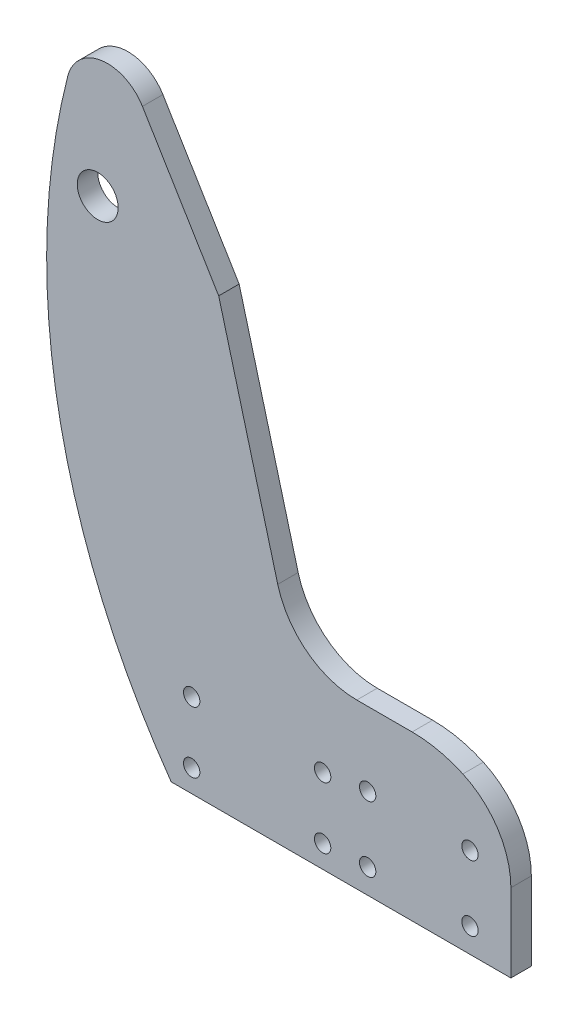
SolidWorks part; units mm, degrees
ref_plane "前视基准面" through (0, 0, 0) normal (0, 0, 1) x (1, 0, 0)
ref_plane "上视基准面" through (0, 0, 0) normal (0, 1, 0) x (1, 0, 0)
ref_plane "右视基准面" through (0, 0, 0) normal (1, 0, 0) x (0, 0, -1)
sketch "草图1" plane through (0, 0, 0) normal (0, 0, 1) x (1, 0, 0)
  line L1 (41.5, -14) -> (-41.5, -14)
  line L2 (41.5, -14) -> (41.5, 14)
  line L3 (41.5, 14) -> (-41.5, 14)
  line L4 (-41.5, -14) -> (-41.5, 14)
  line L5 (41.5, -14) -> (-41.5, 14) construction
  line L6 (41.5, 14) -> (-41.5, -14) construction
  point P0 (0, 0)
  dimension "D1" = 28
  dimension "D2" = 83
extrude "凸台-拉伸1" add sketch "草图1" along normal blind 5
sketch "草图2" plane through (0, 0, 5) normal (0, 0, 1) x (1, 0, 0)
  line L0 (-41.5, -14) -> (41.5, -14) construction
  line L1 (41.5, 14) -> (-41.5, 14) construction
  line L2 (41.5, -14) -> (41.5, 14) construction
  circle A0 centre (6.5, 8) radius 2
  circle A1 centre (31.5, 8) radius 2
  circle A2 centre (31.5, -8) radius 2
  circle A3 centre (6.5, -8) radius 2
  dimension "D1" = 25
  dimension "D2" = 25
  dimension "D3" = 6
  dimension "D4" = 6
  dimension "D5" = 10
  dimension "D6" = 10
  dimension "D7" = 4
  dimension "D8" = 4
  dimension "D9" = 4
  dimension "D10" = 4
  dimension "D11" = 6
  dimension "D12" = 6
extrude "切除-拉伸1" cut sketch "草图2" against normal through all
sketch "草图3" plane through (0, 0, 0) normal (0, 0, -1) x (-1, 0, 0)
  line L0 (41.5, 14) -> (59.7703, 144)
  line L1 (59.7703, 144) -> (29.5, 94)
  line L2 (29.5, 94) -> (-41.5, 14)
  line L3 (-41.5, 14) -> (41.5, 14) construction
  line L4 (41.5, 14) -> (-41.5, 14)
  line L5 (41.5, 14) -> (41.5, -14) construction
  dimension "D1" = 98
  dimension "D2" = 130
  dimension "D3" = 80
  dimension "D4" = 12
extrude "凸台-拉伸2" add sketch "草图3" against normal blind 5
sketch "草图5" plane through (0, 0, 5) normal (0, 0, 1) x (1, 0, 0)
  line L0 (36.5, 26) -> (-11.5, 26)
  line L1 (41.5, -14) -> (41.5, 14) construction
  line L2 (-35.6025, 115.9516) -> (36.5, 26)
  line L3 (-41.5, -14) -> (41.5, -14) construction
  line L5 (-35.6025, 115.9516) -> (-11.5, 26)
  point P6 (-40.6025, 113.9516)
  dimension "D1" = 40
  dimension "D2" = 53
  dimension "D3" = 105
extrude "切除-拉伸3" cut sketch "草图5" against normal through all
fillet "圆角4" radius 30 1 edges at (30.85, 26, 2.5)
fillet "圆角5" radius 20 1 edges at (-11.5, 26, 2.5)
sketch "草图6" plane through (0, 0, 5) normal (0, 0, 1) x (1, 0, 0)
  line L0 (-41.5, 14) -> (-41.5, -14) construction
  line L1 (-41.5, -14) -> (41.5, -14) construction
  circle A0 centre (-36.5, -8.5) radius 2
  circle A1 centre (-4.5, -8.5) radius 2
  circle A2 centre (-4.5, 6.5) radius 2
  circle A3 centre (-36.5, 6.5) radius 2
  dimension "D1" = 5
  dimension "D2" = 37
  dimension "D3" = 37
  dimension "D4" = 5
  dimension "D5" = 15
  dimension "D6" = 15
  dimension "D7" = 4
  dimension "D8" = 4
  dimension "D9" = 4
  dimension "D10" = 4
  dimension "D11" = 5.5
  dimension "D12" = 5.5
extrude "切除-拉伸4" cut sketch "草图6" against normal through all
sketch "草图7" plane through (0, 0, 5) normal (0, 0, 1) x (1, 0, 0)
  line L0 (-41.5, 14) -> (-41.5, -14) construction
  line L1 (-41.5, 14) -> (-59.7703, 144) construction
  line L2 (-41.5, 14) -> (-41.5, -14)
  line L3 (-41.5, 14) -> (-59.7703, 144)
  arc A0 (-59.7703, 144) -> (-41.5, -14) centre (93.7265, 81.6932) ccw
extrude "凸台-拉伸3" add sketch "草图7" against normal blind 5
fillet "圆角7" radius 10 1 edges at (-59.7703, 144, 2.5)
sketch "草图8" plane through (0, 0, 5) normal (0, 0, 1) x (1, 0, 0)
  line L0 (-48.5283, 125.4307) -> (-29.8957, 94.6536) construction
  line L1 (-41.5, -14) -> (41.5, -14) construction
  circle A0 centre (-59.4554, 101) radius 5
  dimension "D1" = 22
  dimension "D2" = 115
  dimension "D3" = 10
extrude "切除-拉伸5" cut sketch "草图8" against normal through all
fillet "圆角8" radius 20 1 edges at (41.5, 14, 2.5)
